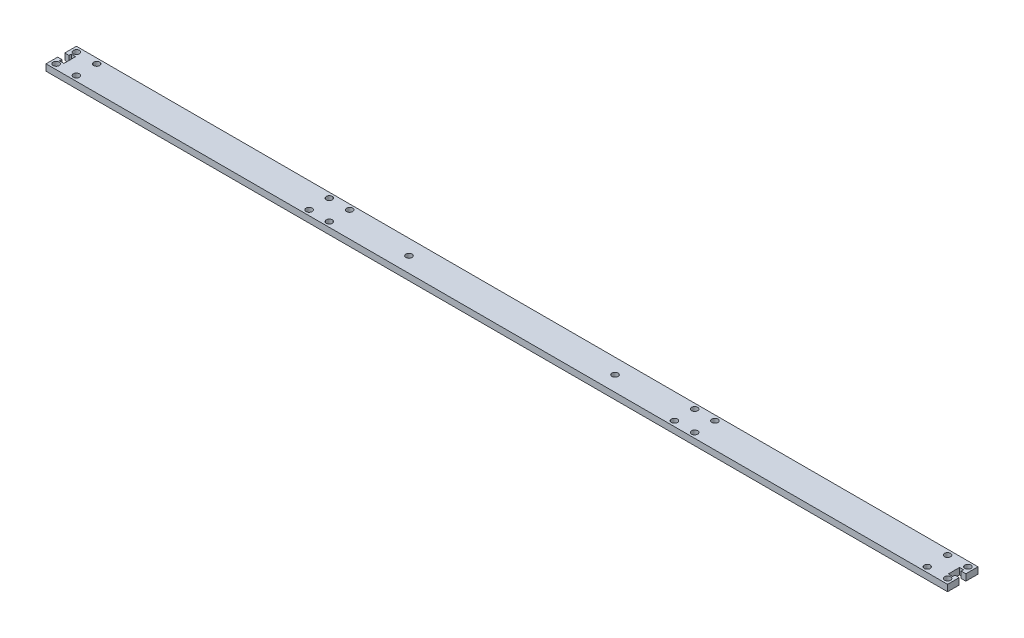
SolidWorks part; units mm, degrees
ref_plane "Front Plane" through (0, 0, 0) normal (0, 0, 1) x (1, 0, 0)
ref_plane "Top Plane" through (0, 0, 0) normal (0, 1, 0) x (1, 0, 0)
ref_plane "Right Plane" through (0, 0, 0) normal (1, 0, 0) x (0, 0, -1)
sketch "Sketch1" plane through (0, 0, 0) normal (0, 1, 0) x (1, 0, 0)
  line L0 (139.7, 7.5) -> (132.2, 7.5)
  line L1 (0, 0) -> (139.7, 0)
  line L2 (0, 0) -> (0, 15)
  line L3 (0, 15) -> (139.7, 15)
  line L4 (139.7, 0) -> (139.7, 15)
  line L5 (0, 7.5) -> (7.5, 7.5)
  line L6 (7.5, 7.5) -> (7.5, 12.5)
  line L7 (7.5, 12.5) -> (2.5, 12.5)
  line L8 (7.5, 12.5) -> (12.5, 12.5)
  line L9 (7.5, 7.5) -> (7.5, 2.5)
  line L10 (7.5, 2.5) -> (2.5, 2.5)
  line L11 (7.5, 2.5) -> (12.5, 2.5)
  line L12 (69.85, 0) -> (69.85, 15)
  line L13 (139.7, 0) -> (139.7, 15)
  line L14 (139.7, 0) -> (304.8, 0)
  line L15 (139.7, 15) -> (304.8, 15)
  line L16 (222.25, 0) -> (222.25, 15)
  line L17 (304.8, 0) -> (304.8, 15)
  line L18 (444.5, 15) -> (304.8, 15)
  line L19 (304.8, 0) -> (304.8, 15)
  line L20 (444.5, 0) -> (304.8, 0)
  line L21 (444.5, 0) -> (444.5, 15)
  line L22 (222.25, 7.5) -> (273.05, 7.5)
  line L23 (222.25, 7.5) -> (171.45, 7.5)
  circle A0 centre (2.5, 2.5) radius 1.5
  circle A1 centre (2.5, 12.5) radius 1.5
  circle A2 centre (12.5, 12.5) radius 1.5
  circle A3 centre (12.5, 2.5) radius 1.5
  circle A4 centre (137.2, 12.5) radius 1.5
  circle A5 centre (127.2, 12.5) radius 1.5
  circle A6 centre (137.2, 2.5) radius 1.5
  circle A7 centre (127.2, 2.5) radius 1.5
  circle A8 centre (432, 12.5) radius 1.5
  circle A9 centre (442, 12.5) radius 1.5
  circle A10 centre (442, 2.5) radius 1.5
  circle A11 centre (432, 2.5) radius 1.5
  circle A12 centre (307.3, 12.5) radius 1.5
  circle A13 centre (317.3, 12.5) radius 1.5
  circle A14 centre (317.3, 2.5) radius 1.5
  circle A15 centre (307.3, 2.5) radius 1.5
  circle A16 centre (273.05, 7.5) radius 1.5
  circle A17 centre (171.45, 7.5) radius 1.5
  dimension "D11" = 82.55
  dimension "D12" = 50.8
  dimension "D1" = 15
  dimension "D2" = 139.7
  dimension "D3" = 7.5
  dimension "D4" = 7.5
  dimension "D5" = 5
  dimension "D6" = 5
  dimension "D7" = 5
  dimension "D8" = 5
  dimension "D9" = 5
  dimension "D10" = 5
  dimension "D13" = 50.8
extrude "Boss-Extrude1" add sketch "Sketch1" along normal blind 3.175
sketch "Sketch4" plane through (0, 3.175, 0) normal (0, 1, 0) x (1, 0, 0)
  line L0 (444.5, 7.5) -> (432.4339, 7.5)
  line L1 (444.5, 0) -> (444.5, 15) construction
  line L2 (0, 15) -> (444.5, 15) construction
  line L3 (222.25, 15) -> (222.25, 0)
  line L4 (0, 0) -> (444.5, 0) construction
  line L5 (444.5, 9) -> (442.2, 9)
  line L6 (442.2, 9) -> (442.2, 10.15)
  line L7 (442.2, 10.15) -> (440.5, 10.15)
  line L8 (440.5, 10.15) -> (440.5, 7.5)
  line L9 (444.5, 9.25) -> (442.45, 9.25)
  line L10 (442.45, 9.25) -> (442.45, 10.4)
  line L11 (442.45, 10.4) -> (440.25, 10.4)
  line L12 (440.25, 10.4) -> (440.25, 7.5)
  line L13 (444.5, 5.75) -> (442.45, 5.75)
  line L14 (442.45, 5.75) -> (442.45, 4.6)
  line L15 (442.45, 4.6) -> (440.25, 4.6)
  line L16 (440.25, 4.6) -> (440.25, 7.5)
  line L17 (0, 9.25) -> (2.05, 9.25)
  line L18 (2.05, 9.25) -> (2.05, 10.4)
  line L19 (0, 5.75) -> (2.05, 5.75)
  line L20 (2.05, 5.75) -> (2.05, 4.6)
  line L21 (2.05, 4.6) -> (4.25, 4.6)
  line L22 (4.25, 4.6) -> (4.25, 7.5)
  line L23 (4.25, 10.4) -> (4.25, 7.5)
  line L24 (2.05, 10.4) -> (4.25, 10.4)
  line L25 (0, 9.25) -> (0, 5.75)
  line L26 (444.5, 9.25) -> (444.5, 5.75)
  line M20 (0, 15) -> (0, 0)
  line M22 (444.5, 0) -> (444.5, 15)
  dimension "D1" = 1.5
  dimension "D2" = 1.15
  dimension "D3" = 1.7
  dimension "D4" = 2.65
  dimension "D5" = 2.3
  dimension "D6" = 0.25
extrude "Cut-Extrude2" cut sketch "Sketch4" against normal blind 10 contours L16 L15 L14 L13 L0 M22 | L7 L8 L0 L5 L6 M22 | L24 L18 L17 L19 L20 L21 L22 L23 M20
sketch "Sketch6" plane through (440.5, 0, 0) normal (1, 0, 0) x (0, 0, -1)
  line L0 (10.15, 0) -> (7.5, 0) construction
  line L5 (7.5, 3.175) -> (10.15, 3.175)
  line L6 (7.5, 3.175) -> (7.5, 0)
  line L7 (7.5, 0) -> (10.15, 0)
  line L8 (10.15, 3.175) -> (10.15, 0)
extrude "Cut-Extrude3" cut sketch "Sketch6" against normal blind 0.25
